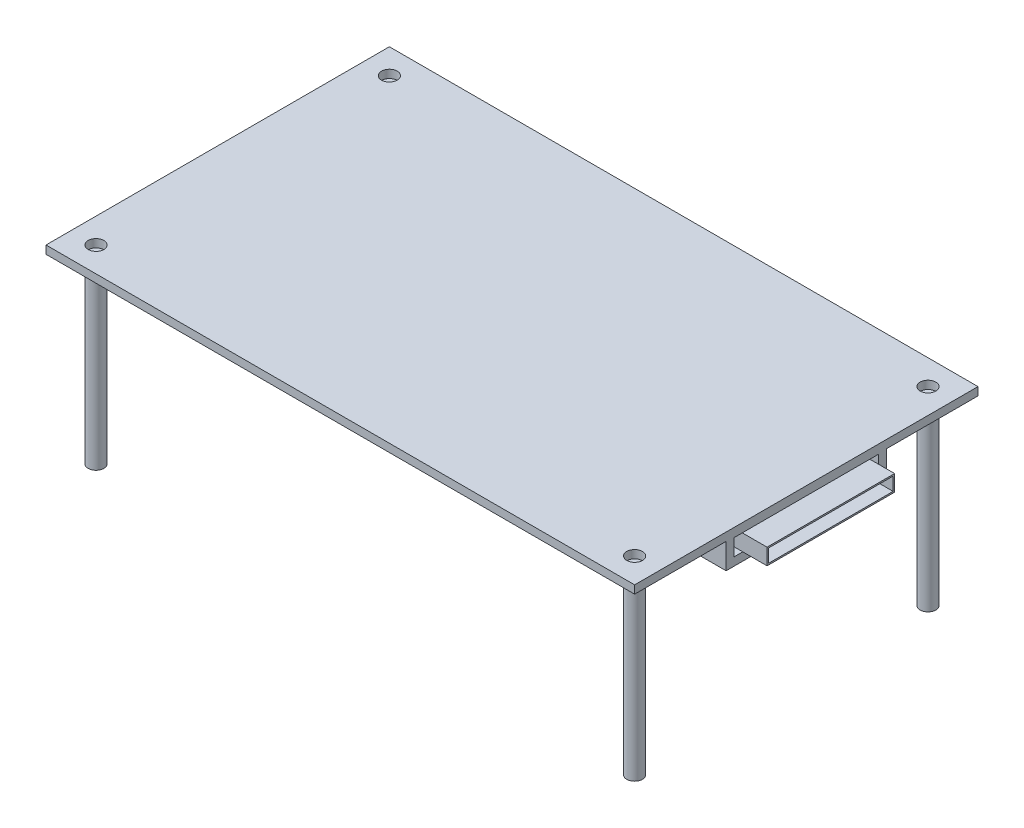
SolidWorks part; units mm, degrees
ref_plane "Alzado" through (0, 0, 0) normal (0, 0, 1) x (1, 0, 0)
ref_plane "Planta" through (0, 0, 0) normal (0, 1, 0) x (1, 0, 0)
ref_plane "Vista lateral" through (0, 0, 0) normal (1, 0, 0) x (0, 0, -1)
sketch "Sketch1" plane through (0, 0, 0) normal (1, 0, 0) x (0, 0, -1)
  line L0 (-35, 1.85) -> (-16.35, 1.85)
  line L2 (-16.35, 1.85) -> (-16.35, -3.35)
  line L3 (-16.35, -3.35) -> (16.35, -3.35)
  line L4 (16.35, 1.85) -> (16.35, -3.35)
  line L7 (-14.7, 1.7) -> (14.7, 1.7)
  line L8 (-14.7, 1.7) -> (-14.7, -1.7)
  line L9 (-14.7, -1.7) -> (14.7, -1.7)
  line L10 (14.7, 1.7) -> (14.7, -1.7)
  line L13 (35, 1.85) -> (35, 3.5)
  line L14 (35, 3.5) -> (-35, 3.5)
  line L15 (-35, 3.5) -> (-35, 1.85)
  line L16 (16.35, 1.85) -> (35, 1.85)
  point P0 (0, 0)
  point P5 (0, 0)
  point P13 (0, 3.5)
  point P14 (-14.7, 0)
  point P17 (0, -3.35)
  point P18 (0, 0)
  point P19 (-16.35, -3.35)
  dimension "D1" = 32.7
  dimension "D2" = 5.2
  dimension "D3" = 1.8
  dimension "D4" = 1.65
  dimension "D5" = 70
  dimension "D6" = 1.65
  dimension "D7" = 1.65
  dimension "D8" = 1.65
extrude "Boss-Extrude1" add sketch "Sketch1" along normal mid plane 120 contours L14 L15 L0 L13 | L4 L0 L2 L3 L7 L10 L9 L8
sketch "Sketch2" plane through (0, 3.5, 0) normal (0, 1, 0) x (1, 0, 0)
  line L1 (60, -35) -> (-60, -35) construction
  line L2 (60, 35) -> (60, -35) construction
  line L3 (-60, 35) -> (-60, -35) construction
  line L4 (60, 35) -> (-60, 35) construction
  circle A0 centre (54.9, -29.9) radius 1.6
  circle A1 centre (-54.9, -29.9) radius 1.6
  circle A2 centre (-54.9, 29.9) radius 1.6
  circle A3 centre (54.9, 29.9) radius 1.6
  point P6 (54.4, 30.8)
  point P7 (54.4, 30.8)
  point P8 (54.5862, 32.5816)
  point P15 (-57.6, 30.3)
  point P16 (-55.9913, -30.467)
  point P17 (54.4, 30.8)
  point P18 (0, 0)
  point P19 (54.4, 32.6)
  point P20 (-54.4, 30.8)
  point P21 (54.4, 30.8)
  point P22 (0, 0)
  point P23 (56, -29.4)
  point P24 (0, 0)
  point P25 (0, 0)
  point P26 (54.4, -31)
  point P27 (-54.2, -29.4)
  point P28 (51, -29.4)
  point P29 (-52.8, -29.4)
  point P32 (57.4, -29.4)
  point P33 (55.8, -31)
  point P36 (57.4, -29.9)
  point P37 (54.9, 30.1)
  point P38 (54.9, 30.1)
  point P39 (-54.9, 29.9)
  point P41 (54.9, 31.7)
  point P42 (-53.3, -29.9)
  point P43 (-53.3, 29.9)
  point P44 (53.3189, 30.1455)
  dimension "D2" = 3.5
  dimension "D3" = 3.5
  dimension "D4" = 3.2
  dimension "D7" = 3.5
  dimension "D8" = 106.6
  dimension "D9" = 59.8
  dimension "D1" = 3.5
  dimension "D5" = 2
  dimension "D6" = 2
extrude "Cut-Extrude2" cut sketch "Sketch2" against normal up to surface (1.65 mm away) contours A2 | A1 | A0 | A3 up to face at (0, 1.85, 25.675)
sketch "Sketch3" plane through (60, 0, 0) normal (1, 0, 0) x (0, 0, -1)
  line L1 (-13, 1.65) -> (13, 1.65)
  line L2 (-13, 1.65) -> (-13, -1.65)
  line L3 (-13, -1.65) -> (13, -1.65)
  line L4 (13, 1.65) -> (13, -1.65)
  line L5 (-13, 1.65) -> (13, -1.65) construction
  line L6 (-13, -1.65) -> (13, 1.65) construction
  line L7 (-12.7, 1.35) -> (12.7, 1.35)
  line L8 (-12.7, 1.35) -> (-12.7, -1.35)
  line L9 (-12.7, -1.35) -> (12.7, -1.35)
  line L10 (12.7, 1.35) -> (12.7, -1.35)
  line L11 (-12.7, 1.35) -> (12.7, -1.35) construction
  line L12 (-12.7, -1.35) -> (12.7, 1.35) construction
  point P0 (0, 0)
  point P5 (0, 0)
  point P11 (13, 0)
  dimension "D1" = 26
  dimension "D2" = 3.3
  dimension "D3" = 0.3
  dimension "D4" = 0.3
extrude "Boss-Extrude2" add sketch "Sketch3" along normal blind 5 and the other way blind 5 separate body
sketch "Sketch4" plane through (0, 1.85, 0) normal (0, -1, 0) x (1, 0, 0)
  circle A0 centre (-54.9, -29.9) radius 1.6 construction
  circle A1 centre (54.9, -29.9) radius 1.6 construction
  circle A2 centre (54.9, 29.9) radius 1.6 construction
  circle A3 centre (-54.9, 29.9) radius 1.6 construction
  circle A4 centre (-54.9, -29.9) radius 1.6
  circle A5 centre (54.9, -29.9) radius 1.6
  circle A6 centre (54.9, 29.9) radius 1.6
  circle A7 centre (-54.9, 29.9) radius 1.6
extrude "Boss-Extrude3" add sketch "Sketch4" along normal blind 37 separate body
